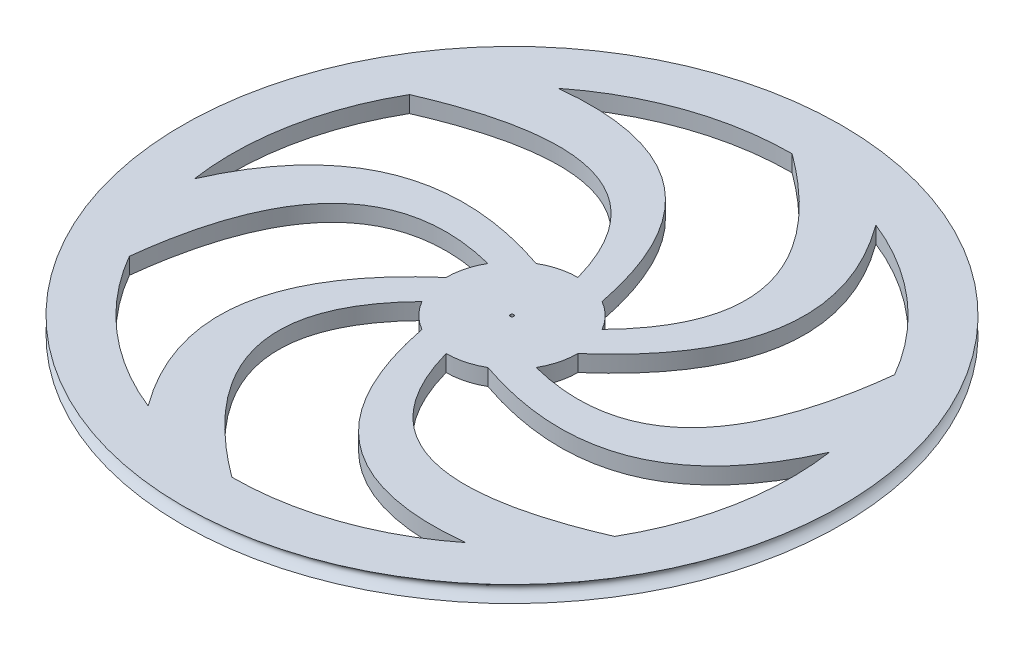
SolidWorks part; units mm, degrees
ref_plane "Front Plane" through (0, 0, 0) normal (0, 0, 1) x (1, 0, 0)
ref_plane "Top Plane" through (0, 0, 0) normal (0, 1, 0) x (1, 0, 0)
ref_plane "Right Plane" through (0, 0, 0) normal (1, 0, 0) x (0, 0, -1)
sketch "Sketch1" plane through (0, 0, 0) normal (0, 1, 0) x (1, 0, 0)
  line L0 (0, 0) -> (0, 53.975)
  line L1 (0, 0) -> (46.7437, 26.9875)
  line L2 (0, 0) -> (38.1661, 38.1661)
  line L3 (0, 0) -> (46.7437, -26.9875)
  line L4 (0, 0) -> (53.975, 0)
  line L5 (19.083, 19.083) -> (38.1661, 38.1661)
  circle A0 centre (0, 0) radius 63.5
  circle A1 centre (0, 0) radius 53.975
  circle A2 centre (0, 0) radius 12.7
  circle A3 centre (0, 0) radius 0.3175
  spline S0 degree 2 poles (10.9985, 6.35) (33.3601, 29.2535) (0, 53.975) knots 0 0 0 1 1 1
  spline S1 degree 2 poles (12.7, 0) (39.5573, 23.4186) (19.9618, 50.1481) knots 0 0 0 1 1 1
  spline S2 degree 2 poles (10.9985, -6.35) (42.0143, -14.264) (46.7437, 26.9875) knots 0 0 0 1 1 1
  spline S3 degree 2 poles (6.35, -10.9985) (40.0598, -22.5483) (53.4104, 7.7866) knots 0 0 0 1 1 1
  spline S4 degree 2 poles (0, -12.7) (8.6542, -43.5175) (46.7437, -26.9875) knots 0 0 0 1 1 1
  spline S5 degree 2 poles (-6.35, -10.9985) (0.5025, -45.9669) (33.4486, -42.3614) knots 0 0 0 1 1 1
  spline S6 degree 2 poles (-10.9985, -6.35) (-33.3601, -29.2535) (0, -53.975) knots 0 0 0 1 1 1
  spline S7 degree 2 poles (-12.7, 0) (-39.5573, -23.4186) (-19.9618, -50.1481) knots 0 0 0 1 1 1
  spline S8 degree 2 poles (-10.9985, 6.35) (-42.0143, 14.264) (-46.7437, -26.9875) knots 0 0 0 1 1 1
  spline S9 degree 2 poles (-6.35, 10.9985) (-40.0598, 22.5483) (-53.4104, -7.7866) knots 0 0 0 1 1 1
  spline S10 degree 2 poles (0, 12.7) (-8.6542, 43.5175) (-46.7437, 26.9875) knots 0 0 0 1 1 1
  spline S11 degree 2 poles (6.35, 10.9985) (-0.5025, 45.9669) (-33.4486, 42.3614) knots 0 0 0 1 1 1
  point P49 (0, 0)
sketch "Sketch2" plane through (0, 0, 0) normal (0, 0, 1) x (1, 0, 0)
  line L0 (0, 0) -> (-63.5, 0)
  line L1 (63.5, 0) -> (-63.5, 0) construction
  line L2 (-63.5, 0) -> (-63.5, 3.175)
  line L3 (-63.5, 1.5875) -> (-61.9125, 1.5875)
  line L4 (0, 0) -> (0, 30.3686) construction
  spline S0 degree 2 poles (-63.5, 3.175) (-60.325, 1.5875) (-63.5, 0) knots 0 0 0 1 1 1
extrude "Boss-Extrude1" add sketch "Sketch1" along normal blind 3.175 contours A0 A1 | L0 S11 A1 S10 | A2 S11 L0 | L2 S1 A1 S0 | L1 S1 L2 S0 | A2 S1 L1 | L4 S3 A1 S2 | L3 S3 L4 S2 | A2 S3 L3 | L0 A2 L3 | L3 A2 L4 | L4 A2 L1 | L1 A2 L2 | L2 A2 L0 | A2 S9 A1 S8 | A2 S7 A1 S6 | A2 S5 A1 S4
revolve "Cut-Revolve2" cut sketch "Sketch2" angle 360 about L4
